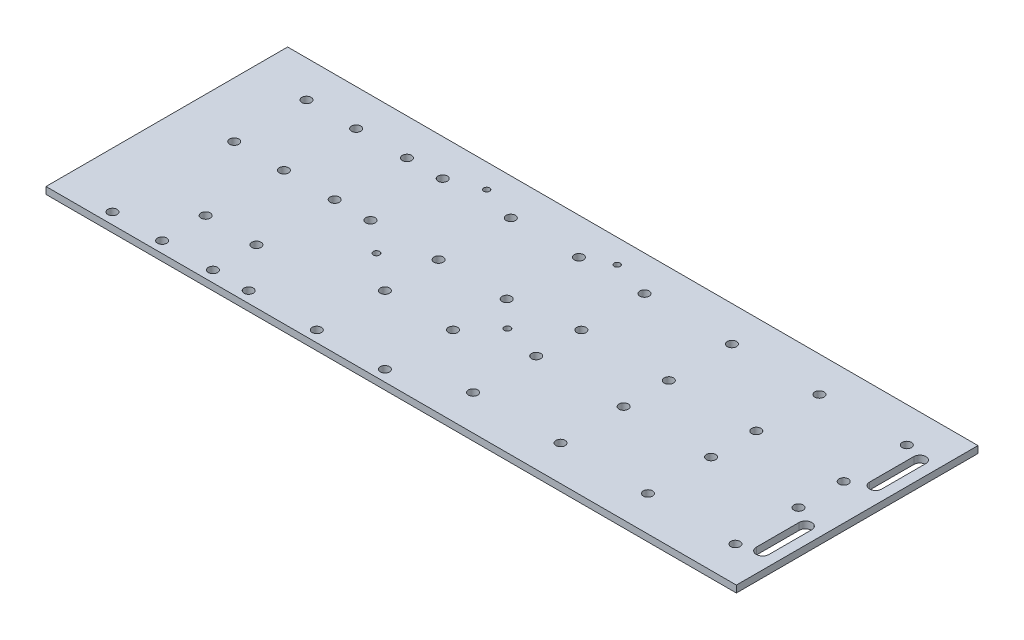
SolidWorks part; units mm, degrees
ref_plane "Front Plane" through (0, 0, 0) normal (0, 0, 1) x (1, 0, 0)
ref_plane "Top Plane" through (0, 0, 0) normal (0, 1, 0) x (1, 0, 0)
ref_plane "Right Plane" through (0, 0, 0) normal (1, 0, 0) x (0, 0, -1)
sketch "Sketch1" plane through (0, 0, 0) normal (1, 0, 0) x (0, 0, -1)
  line L1 (-52.5, -1.5) -> (52.5, -1.5)
  line L2 (-52.5, -1.5) -> (-52.5, 1.5)
  line L3 (-52.5, 1.5) -> (52.5, 1.5)
  line L4 (52.5, -1.5) -> (52.5, 1.5)
  line L5 (-52.5, -1.5) -> (52.5, 1.5) construction
  line L6 (-52.5, 1.5) -> (52.5, -1.5) construction
  point P0 (0, 0)
  dimension "D1" = 105
  dimension "D2" = 3
extrude "Boss-Extrude1" add sketch "Sketch1" against normal blind 300
sketch "Sketch2" plane through (0, -1.5, 0) normal (0, -1, 0) x (1, 0, 0)
  line L0 (-126, 0) -> (-94, 0) construction
  line L1 (-7.1868, -34.404) -> (-7.1868, -15.2037) construction
  line L2 (-9.8195, -34.404) -> (-9.8195, -15.2037)
  line L3 (-4.5541, -34.404) -> (-4.5541, -15.2037)
  line L4 (-7.1868, 33.9165) -> (-7.1868, 15.3175) construction
  line L5 (-4.4308, 33.9165) -> (-4.4308, 15.3175)
  line L6 (-9.9428, 33.9165) -> (-9.9428, 15.3175)
  circle A0 centre (-187.1742, 18.0526) radius 2
  circle A1 centre (-157.5742, 18.0526) radius 2
  circle A2 centre (-157.5742, 47.6526) radius 2
  circle A3 centre (-187.1742, 47.6526) radius 2
  circle A4 centre (-203.0803, 5.824) radius 1.3749
  circle A5 centre (-146.2893, 5.7138) radius 1.3542
  circle A6 centre (-146.4355, -42.1417) radius 1.3076
  circle A7 centre (-203.0803, -42.0712) radius 1.2739
  circle A8 centre (-157.5742, -36.6542) radius 2
  circle A9 centre (-187.1742, -36.6542) radius 2
  circle A10 centre (-216.7742, -36.6542) radius 2
  circle A11 centre (-91.671, 37.2476) radius 2
  circle A12 centre (-216.7742, 47.6526) radius 2
  circle A13 centre (-254.3888, 47.6526) radius 2
  circle A14 centre (-275.9742, 47.6526) radius 2
  circle A15 centre (-157.5742, -5.2727) radius 2
  circle A16 centre (-187.1742, -5.2727) radius 2
  circle A17 centre (-216.7742, -5.2727) radius 2
  circle A18 centre (-232.3136, 47.6526) radius 2
  circle A19 centre (-275.9742, -5.2727) radius 2
  circle A20 centre (-275.9742, -36.6542) radius 2
  circle A21 centre (-232.3136, -5.2727) radius 2
  circle A22 centre (-232.3136, 28.7479) radius 2
  circle A23 centre (-254.3888, 28.7479) radius 2
  circle A24 centre (-254.3888, -5.2727) radius 2
  circle A25 centre (-246.3742, -5.2727) radius 2 [skipped]
  circle A26 centre (-246.3742, 47.6526) radius 2 [skipped]
  circle A27 centre (-254.3888, -36.6542) radius 2
  circle A28 centre (-232.3136, -36.6542) radius 2
  circle A29 centre (-246.3742, -36.6542) radius 2 [skipped]
  circle A30 centre (-53.671, 37.2476) radius 2
  circle A31 centre (-15.671, 37.2476) radius 2
  circle A32 centre (-129.671, 37.2476) radius 2
  circle A33 centre (-129.671, 9.8217) radius 2
  circle A34 centre (-91.671, 9.8217) radius 2
  circle A35 centre (-53.671, 9.8217) radius 2
  circle A36 centre (-15.671, 9.8217) radius 2
  circle A37 centre (-129.671, -37.2476) radius 2
  circle A38 centre (-129.671, -9.8217) radius 2
  circle A39 centre (-91.671, -9.8217) radius 2
  circle A40 centre (-53.671, -9.8217) radius 2
  circle A41 centre (-15.671, -9.8217) radius 2
  arc A42 (-9.8195, -34.404) -> (-4.5541, -34.404) centre (-7.1868, -34.404) ccw
  arc A43 (-4.5541, -15.2037) -> (-9.8195, -15.2037) centre (-7.1868, -15.2037) ccw
  arc A44 (-4.4308, 33.9165) -> (-9.9428, 33.9165) centre (-7.1868, 33.9165) ccw
  arc A45 (-9.9428, 15.3175) -> (-4.4308, 15.3175) centre (-7.1868, 15.3175) ccw
  circle A85 centre (-91.671, -37.2476) radius 2
  circle A86 centre (-53.671, -37.2476) radius 2
  circle A87 centre (-15.671, -37.2476) radius 2
  circle A88 centre (22.329, -9.8217) radius 2 [skipped]
  circle A89 centre (60.329, -9.8217) radius 2 [skipped]
  circle A90 centre (98.329, -9.8217) radius 2 [skipped]
  circle A91 centre (288.329, -9.8217) radius 2 [skipped]
  circle A92 centre (326.329, -9.8217) radius 2 [skipped]
  circle A93 centre (364.329, -9.8217) radius 2 [skipped]
  circle A94 centre (402.329, -9.8217) radius 2 [skipped]
  circle A95 centre (440.329, -9.8217) radius 2 [skipped]
  circle A96 centre (478.329, -9.8217) radius 2 [skipped]
  circle A97 centre (516.329, -9.8217) radius 2 [skipped]
  circle A98 centre (554.329, -9.8217) radius 2 [skipped]
  circle A99 centre (592.329, -9.8217) radius 2 [skipped]
  circle A100 centre (630.329, -9.8217) radius 2 [skipped]
  circle A101 centre (668.329, -9.8217) radius 2 [skipped]
  circle A102 centre (706.329, -9.8217) radius 2 [skipped]
  circle A103 centre (744.329, -9.8217) radius 2 [skipped]
  circle A104 centre (782.329, -9.8217) radius 2 [skipped]
  circle A105 centre (820.329, -9.8217) radius 2 [skipped]
  circle A106 centre (858.329, -9.8217) radius 2 [skipped]
  circle A107 centre (896.329, -9.8217) radius 2 [skipped]
  circle A108 centre (934.329, -9.8217) radius 2 [skipped]
  circle A109 centre (972.329, -9.8217) radius 2 [skipped]
  circle A110 centre (1010.329, -9.8217) radius 2 [skipped]
  circle A111 centre (1048.329, -9.8217) radius 2 [skipped]
  circle A112 centre (1086.329, -9.8217) radius 2 [skipped]
  circle A113 centre (1124.329, -9.8217) radius 2 [skipped]
  circle A114 centre (1162.329, -9.8217) radius 2 [skipped]
  circle A115 centre (1200.329, -9.8217) radius 2 [skipped]
  circle A116 centre (1238.329, -9.8217) radius 2 [skipped]
  circle A117 centre (1276.329, -9.8217) radius 2 [skipped]
  circle A118 centre (1314.329, -9.8217) radius 2 [skipped]
  circle A119 centre (1352.329, -9.8217) radius 2 [skipped]
  circle A120 centre (1390.329, -9.8217) radius 2 [skipped]
  circle A121 centre (1428.329, -9.8217) radius 2 [skipped]
  circle A122 centre (1466.329, -9.8217) radius 2 [skipped]
  circle A123 centre (1504.329, -9.8217) radius 2 [skipped]
  circle A124 centre (1542.329, -9.8217) radius 2 [skipped]
  circle A125 centre (1580.329, -9.8217) radius 2 [skipped]
  circle A126 centre (1618.329, -9.8217) radius 2 [skipped]
  circle A127 centre (136.329, -9.8217) radius 2 [skipped]
  circle A128 centre (174.329, -9.8217) radius 2 [skipped]
  circle A129 centre (212.329, -9.8217) radius 2 [skipped]
  circle A130 centre (250.329, -9.8217) radius 2 [skipped]
  point P96 (-7.1868, -24.8038)
  point P103 (-7.1868, 24.617)
  dimension "D3" = 5
  dimension "D4" = 4
  dimension "D5" = 4
  dimension "D7" = 4
  dimension "D9" = 5
  dimension "D10" = 4
  dimension "D6" = 4
  dimension "D11" = 4
  dimension "D12" = 4
  dimension "D13" = 4
  dimension "D14" = 4
  dimension "D18" = 2
  dimension "D20" = 4
  dimension "D16" = 3
  dimension "D21" = 47
  dimension "D22" = 4
extrude "Cut-Extrude1" cut sketch "Sketch2" against normal blind 10
